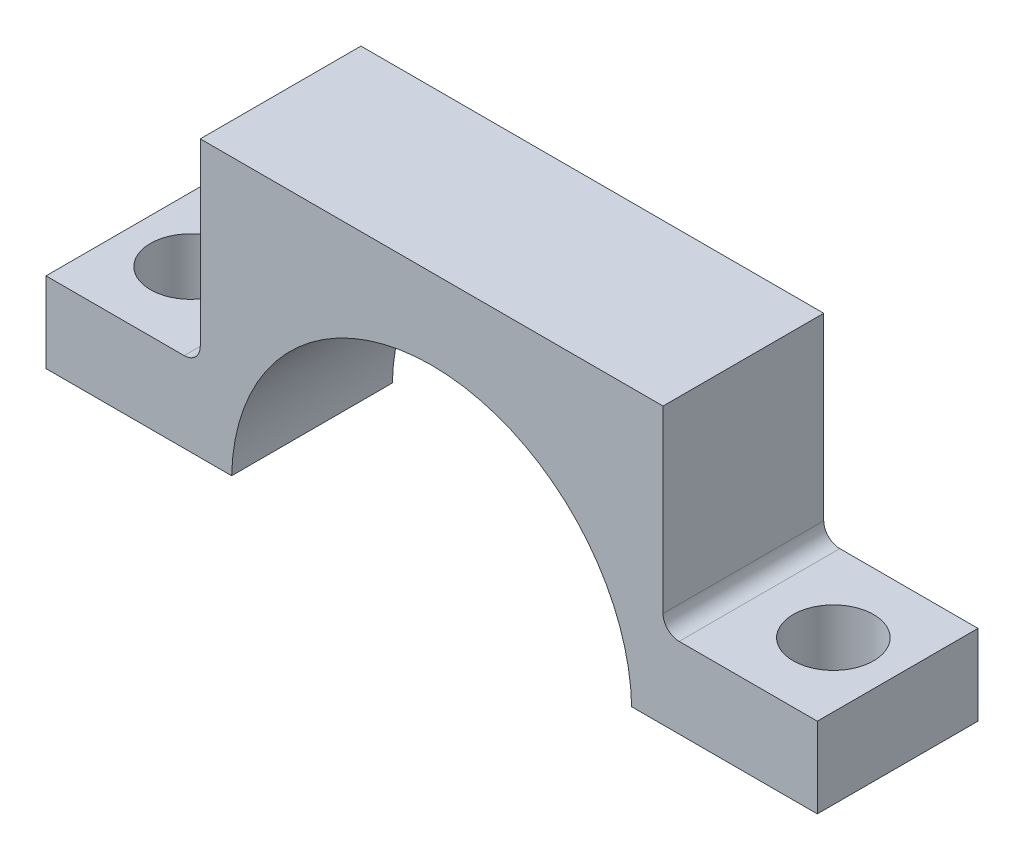
SolidWorks part; units mm, degrees
ref_plane "前视基准面" through (0, 0, 0) normal (0, 0, 1) x (1, 0, 0)
ref_plane "上视基准面" through (0, 0, 0) normal (0, 1, 0) x (1, 0, 0)
ref_plane "右视基准面" through (0, 0, 0) normal (1, 0, 0) x (0, 0, -1)
sketch "草图1" plane through (0, 0, 0) normal (0, 0, 1) x (1, 0, 0)
  line L0 (12.4472, 0.266) -> (14.4, 0.266)
  line L1 (14.4, 0.266) -> (14.4, 17.45)
  line L2 (14.4, 17.45) -> (-14.4, 17.45)
  line L3 (0, 0) -> (0, -7.1949) construction
  line L4 (-14.4, 0.266) -> (-14.4, 17.45)
  line L5 (-14.4, 0.266) -> (-12.4472, 0.266)
  arc A0 (12.4472, 0.266) -> (-12.4472, 0.266) centre (0, 0) ccw
  point P1 (-14.9442, 0.265)
  point P9 (0, 12.45)
  point P12 (0, 0)
  dimension "D1" = 24.9
  dimension "D2" = 28.8
  dimension "D3" = 5
extrude "凸台-拉伸1" add sketch "草图1" along normal mid plane 10
sketch "草图3" plane through (0, 0.266, 0) normal (0, -1, 0) x (1, 0, 0)
  line L0 (14.4, 5) -> (24, 5)
  line L1 (-24, 5) -> (-14.4, 5)
  line L2 (-24, 5) -> (-24, -5)
  line L3 (-24, -5) -> (-14.4, -5)
  line L4 (24, 5) -> (24, -5)
  line L5 (0, -5) -> (0, 0) construction
  line L6 (-24, 0) -> (0, 0) construction
  line L8 (-14.4, 5) -> (-14.4, -5)
  line L10 (14.4, 5) -> (14.4, -5)
  line L11 (0, -5) -> (0, 0) construction
  line L12 (-14.4, 0) -> (0, 0) construction
  line L13 (14.4, 0) -> (24, 0) construction
  line L14 (14.4, -5) -> (24, -5)
  circle A0 centre (-20, 0) radius 2.5
  circle A1 centre (20, 0) radius 2.5
  point P0 (0, 0)
  point P8 (0, 0)
  dimension "D4" = 5
  dimension "D2" = 48
  dimension "D3" = 20
extrude "凸台-拉伸2" add sketch "草图3" against normal blind 5
fillet "圆角1" radius 1 2 edges at (14.4, 5.266, 0) (-14.4, 5.266, 0)
